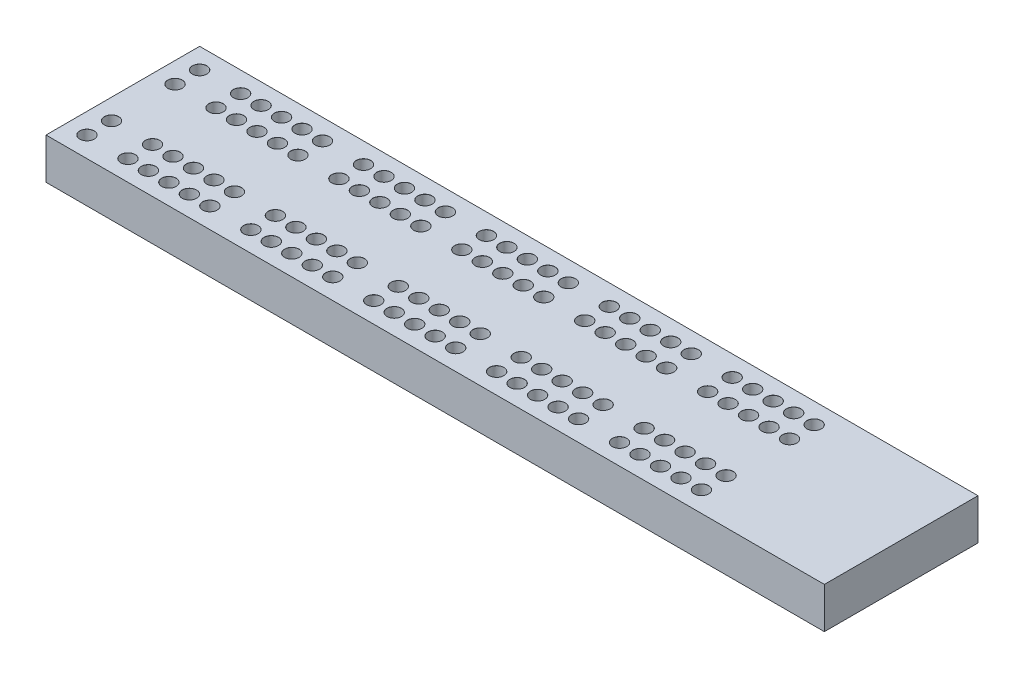
SolidWorks part; units mm, degrees
ref_plane "Front Plane" through (0, 0, 0) normal (0, 0, 1) x (1, 0, 0)
ref_plane "Top Plane" through (0, 0, 0) normal (0, 1, 0) x (1, 0, 0)
ref_plane "Right Plane" through (0, 0, 0) normal (1, 0, 0) x (0, 0, -1)
sketch "Sketch1" plane through (0, 0, 0) normal (0, 1, 0) x (1, 0, 0)
  line L1 (-190, -37.5) -> (190, -37.5)
  line L2 (-190, -37.5) -> (-190, 37.5)
  line L3 (-190, 37.5) -> (190, 37.5)
  line L4 (190, -37.5) -> (190, 37.5)
  line L5 (-190, -37.5) -> (190, 37.5) construction
  line L6 (-190, 37.5) -> (190, -37.5) construction
  point P0 (0, 0)
  dimension "D1" = 75
  dimension "D2" = 380
extrude "Boss-Extrude1" add sketch "Sketch1" along normal blind 20
hole_wizard "Ø7.0 (7) Diameter Hole1" positions "3DSketch1" profile "Sketch3" hole size "Ø7.0" standard "ANSI Metric"
sketch3d "3DSketch1"
  line L0 (190, 20, -37.5) -> (-190, 20, -37.5) construction
  line L1 (-190, 20, -37.5) -> (-190, 20, 37.5) construction
  point P0 (-180, 20, -27.5)
  dimension "D1" = 10
  dimension "D2" = 10
sketch "Sketch3" plane through (-180, 20, -27.5) normal (1, 0, 0) x (0, 0, 1)
  line L0 (0, 0) -> (0, 14.103)
  line L1 (0, 14.103) -> (3.5, 12)
  line L2 (3.5, 12) -> (3.5, 0.025)
  line L3 (3.5, 0.025) -> (3.525, 0)
  line L5 (3.525, 0) -> (0, 0)
  line L6 (-3.5, 0.025) -> (-3.525, 0) construction
  line L10 (0, 14.103) -> (-3.5, 12) construction
  line L11 (0, -6.35) -> (0, 107.95) construction
  dimension "Hole Dia." = 7
  dimension "Hole Depth" = 12
  dimension "Near C'Sink Dia." = 7.05
  dimension "Near C'Sink Angle" = 90
  dimension "Drill Angle" = 118
pattern_linear "LPattern1" count 31 spacing 10 along (1, 0, 0) count 2 spacing 12 along (0, 0, 1) skipping (1, 0), (1, 1), (7, 0), (7, 1), (13, 0), (13, 1), (19, 0), (19, 1), (25, 0), (25, 1) of "Ø7.0 (7) Diameter Hole1"
mirror "Mirror1" about plane through (0, 0, 0) normal (0, 0, 1) of "LPattern1", "Ø7.0 (7) Diameter Hole1"
